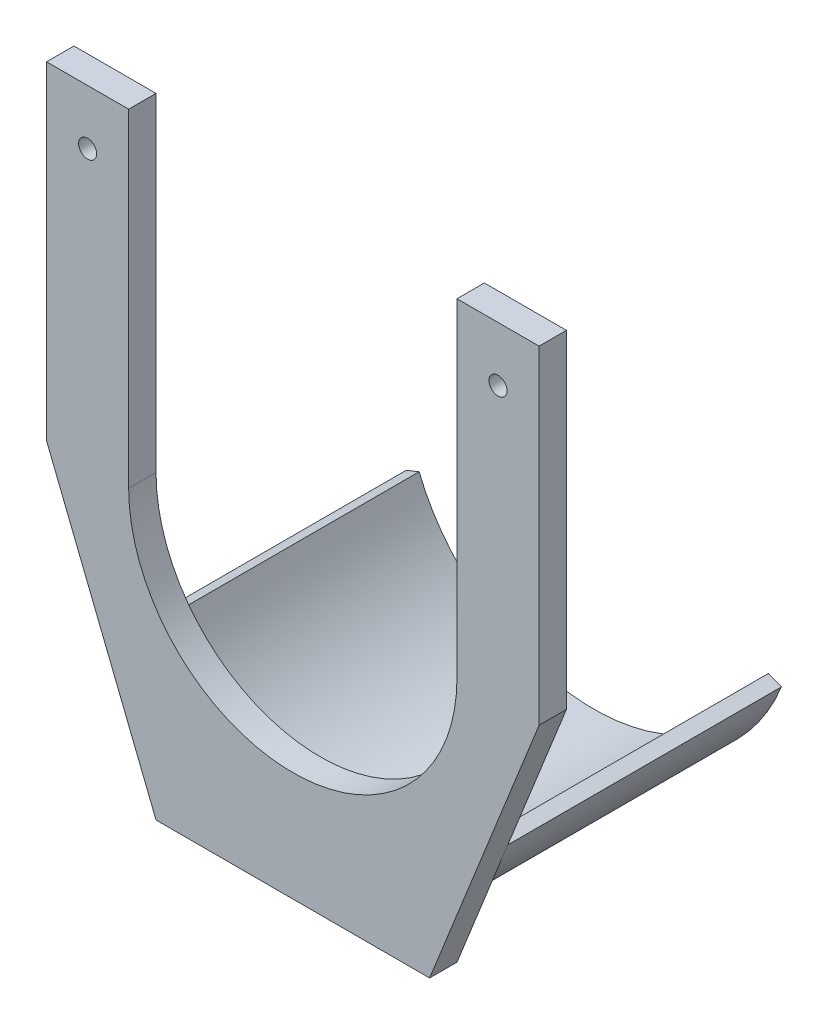
SolidWorks part; units mm, degrees
ref_plane "정면" through (0, 0, 0) normal (0, 0, 1) x (1, 0, 0)
ref_plane "윗면" through (0, 0, 0) normal (0, 1, 0) x (1, 0, 0)
ref_plane "우측면" through (0, 0, 0) normal (1, 0, 0) x (0, 0, -1)
sketch "스케치1" plane through (0, 0, 0) normal (0, 0, 1) x (1, 0, 0)
  line L0 (0, 77.7793) -> (0, -30) construction
  line L1 (-25, -50) -> (25, -50)
  line L2 (-45, 0) -> (-45, 60)
  line L3 (-45, 60) -> (-30, 60)
  line L4 (-30, 0) -> (-30, 60)
  line L5 (30, 0) -> (30, 60)
  line L6 (45, 60) -> (30, 60)
  line L7 (45, 0) -> (45, 60)
  line L9 (-45, 0) -> (-25, -50)
  line L10 (45, 0) -> (25, -50)
  circle A0 centre (-37.5, 50) radius 1.65
  arc A1 (-30, 0) -> (30, 0) centre (0, 0) ccw
  circle A2 centre (37.5, 50) radius 1.65
  dimension "D4" = 50
  dimension "D6" = 3.3
  dimension "D1" = 15
  dimension "D2" = 60
  dimension "D3" = 30
  dimension "D5" = 50
  dimension "D7" = 10
  dimension "D8" = 7.5
extrude "보스-돌출1" add sketch "스케치1" along normal blind 5
sketch "스케치4" plane through (0, 0, 0) normal (0, 0, -1) x (-1, 0, 0)
  line L0 (25, -50) -> (-25, -50) construction
  line L1 (-25, -50) -> (-45, 0) construction
  line L3 (45, 0) -> (25, -50) construction
  line L4 (-31.9166, -25.8408) -> (-34.2848, -26.7881)
  line L5 (0, -13.0742) -> (0, -50) construction
  line L6 (31.9166, -25.8408) -> (34.2848, -26.7881)
  arc A0 (-34.2848, -26.7881) -> (34.2848, -26.7881) centre (0, -13.0742) ccw
  arc A1 (-31.9166, -25.8408) -> (31.9166, -25.8408) centre (0, -13.0742) ccw
extrude "보스-돌출2" add sketch "스케치4" along normal blind 50
